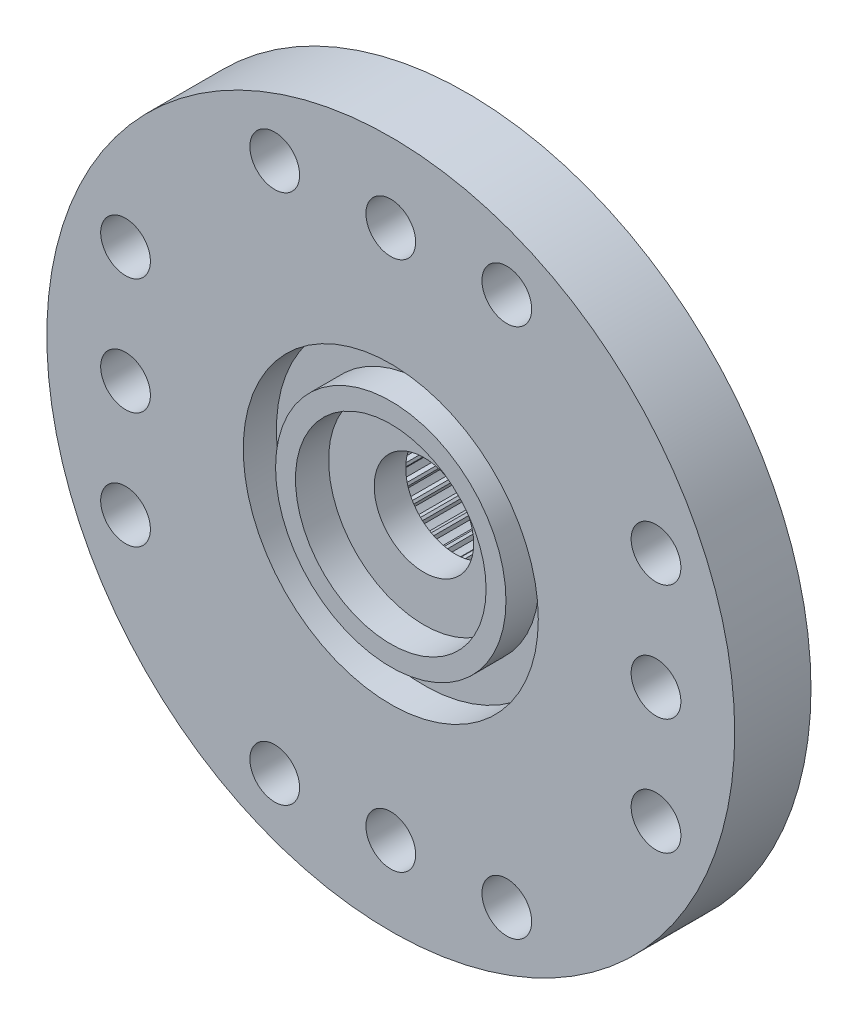
SolidWorks part; units mm, degrees
ref_plane "Plan de face" through (0, 0, 0) normal (0, 0, 1) x (1, 0, 0)
ref_plane "Plan de dessus" through (0, 0, 0) normal (0, 1, 0) x (1, 0, 0)
ref_plane "Plan de droite" through (0, 0, 0) normal (1, 0, 0) x (0, 0, -1)
sketch "Esquisse1" plane through (0, 0, 0) normal (0, 0, 1) x (1, 0, 0)
  circle A10 centre (0, 0) radius 10.375
  dimension "D7" = 20.75
extrude "Boss.-Extru.1" add sketch "Esquisse1" along normal blind 2.3
sketch "Esquisse2" plane through (0, 0, 2.3) normal (0, 0, 1) x (1, 0, 0)
  circle A0 centre (0, 0) radius 4.45
  dimension "D1" = 8.9
extrude "Enlèv. mat.-Extru.1" cut sketch "Esquisse2" against normal blind 1
sketch "Esquisse3" plane through (0, 0, 1.3) normal (0, 0, 1) x (1, 0, 0)
  circle A0 centre (0, 0) radius 2.875
  circle A1 centre (0, 0) radius 3.475
  dimension "D1" = 5.75
  dimension "D2" = 0.6
extrude "Boss.-Extru.2" add sketch "Esquisse3" along normal up to surface (1 mm away) up to face at (4.45, 0, 2.3)
sketch "Esquisse4" plane through (0, 0, 0) normal (0, 0, -1) x (-1, 0, 0)
  circle A0 centre (0, 0) radius 4.4
  dimension "D1" = 8.8
extrude "Boss.-Extru.3" add sketch "Esquisse4" along normal blind 3
sketch "Esquisse5" plane through (0, 0, 1.3) normal (0, 0, 1) x (1, 0, 0)
  circle A0 centre (0, 0) radius 1.5
  dimension "D1" = 3
extrude "Enlèv. mat.-Extru.2" cut sketch "Esquisse5" against normal through all
sketch "Esquisse6" plane through (0, 0, -3) normal (0, 0, -1) x (-1, 0, 0)
  line L0 (-0.1143, 2.9978) -> (-0.0406, 2.8652)
  line L1 (0.0406, 2.8652) -> (0.1143, 2.9978)
  line L2 (0, 2.8652) -> (0, 0) construction
  line L3 (-0.0406, 2.8652) -> (0.0406, 2.8652)
  line L4 (0.439, 2.8316) -> (0.5304, 2.9527)
  line L5 (0.3041, 2.9846) -> (0.3585, 2.8429)
  line L6 (0.3585, 2.8429) -> (0.439, 2.8316)
  line L7 (0.8288, 2.743) -> (0.9362, 2.8502)
  line L8 (0.7165, 2.9132) -> (0.7507, 2.7654)
  line L9 (0.7507, 2.7654) -> (0.8288, 2.743)
  line L10 (1.2025, 2.6009) -> (1.3237, 2.6922)
  line L11 (1.1149, 2.7851) -> (1.1283, 2.634)
  line L12 (1.1283, 2.634) -> (1.2025, 2.6009)
  line L13 (1.5527, 2.4083) -> (1.6855, 2.4817)
  line L14 (1.4917, 2.6029) -> (1.4839, 2.4513)
  line L15 (1.4839, 2.4513) -> (1.5527, 2.4083)
  line L16 (1.8728, 2.1687) -> (2.0145, 2.223)
  line L17 (1.8394, 2.3699) -> (1.8106, 2.2209)
  line L18 (1.8106, 2.2209) -> (1.8728, 2.1687)
  line L19 (2.1564, 1.887) -> (2.3043, 1.921)
  line L20 (2.1514, 2.0909) -> (2.1021, 1.9473)
  line L21 (2.1021, 1.9473) -> (2.1564, 1.887)
  line L22 (2.398, 1.5685) -> (2.5492, 1.5816)
  line L23 (2.4214, 1.7711) -> (2.3526, 1.6358)
  line L24 (2.3526, 1.6358) -> (2.398, 1.5685)
  line L25 (2.593, 1.2195) -> (2.7445, 1.2114)
  line L26 (2.6443, 1.4169) -> (2.5574, 1.2925)
  line L27 (2.5574, 1.2925) -> (2.593, 1.2195)
  line L28 (2.7375, 0.8468) -> (2.8864, 0.8177)
  line L29 (2.8158, 1.0351) -> (2.7124, 0.924)
  line L30 (2.7124, 0.924) -> (2.7375, 0.8468)
  line L31 (2.8287, 0.4575) -> (2.9721, 0.408)
  line L32 (2.9324, 0.6331) -> (2.8146, 0.5375)
  line L33 (2.8146, 0.5375) -> (2.8287, 0.4575)
  line L34 (2.8648, 0.0594) -> (3, -0.0096)
  line L35 (2.992, 0.2188) -> (2.862, 0.1406)
  line L36 (2.862, 0.1406) -> (2.8648, 0.0594)
  line L37 (2.8452, -0.3399) -> (2.9695, -0.427)
  line L38 (2.9933, -0.1997) -> (2.8537, -0.2591)
  line L39 (2.8537, -0.2591) -> (2.8452, -0.3399)
  line L40 (2.7702, -0.7325) -> (2.8811, -0.8361)
  line L41 (2.9364, -0.6144) -> (2.7899, -0.6537)
  line L42 (2.7899, -0.6537) -> (2.7702, -0.7325)
  line L43 (2.6413, -1.111) -> (2.7367, -1.229)
  line L44 (2.8223, -1.017) -> (2.6717, -1.0357)
  line L45 (2.6717, -1.0357) -> (2.6413, -1.111)
  line L46 (2.461, -1.4677) -> (2.5391, -1.5979)
  line L47 (2.6533, -1.3999) -> (2.5016, -1.3974)
  line L48 (2.5016, -1.3974) -> (2.461, -1.4677)
  line L49 (2.2328, -1.796) -> (2.292, -1.9357)
  line L50 (2.4327, -1.7556) -> (2.2828, -1.732)
  line L51 (2.2828, -1.732) -> (2.2328, -1.796)
  line L52 (1.9611, -2.0892) -> (2.0003, -2.2358)
  line L53 (2.1647, -2.0771) -> (2.0195, -2.0328)
  line L54 (2.0195, -2.0328) -> (1.9611, -2.0892)
  line L55 (1.6512, -2.3418) -> (1.6696, -2.4925)
  line L56 (1.8545, -2.3581) -> (1.7169, -2.2941)
  line L57 (1.7169, -2.2941) -> (1.6512, -2.3418)
  line L58 (1.3093, -2.5488) -> (1.3065, -2.7006)
  line L59 (1.5083, -2.5933) -> (1.381, -2.5107)
  line L60 (1.381, -2.5107) -> (1.3093, -2.5488)
  line L61 (0.9418, -2.7063) -> (0.9179, -2.8561)
  line L62 (1.1327, -2.7779) -> (1.0181, -2.6785)
  line L63 (1.0181, -2.6785) -> (0.9418, -2.7063)
  line L64 (0.556, -2.811) -> (0.5115, -2.9561)
  line L65 (0.7351, -2.9086) -> (0.6354, -2.7941)
  line L66 (0.6354, -2.7941) -> (0.556, -2.811)
  line L67 (0.1594, -2.861) -> (0.0951, -2.9985)
  line L68 (0.3231, -2.9825) -> (0.2404, -2.8553)
  line L69 (0.2404, -2.8553) -> (0.1594, -2.861)
  line L70 (-0.2404, -2.8553) -> (-0.3231, -2.9825)
  line L71 (-0.0951, -2.9985) -> (-0.1594, -2.861)
  line L72 (-0.1594, -2.861) -> (-0.2404, -2.8553)
  line L73 (-0.6354, -2.7941) -> (-0.7351, -2.9086)
  line L74 (-0.5115, -2.9561) -> (-0.556, -2.811)
  line L75 (-0.556, -2.811) -> (-0.6354, -2.7941)
  line L76 (-1.0181, -2.6785) -> (-1.1327, -2.7779)
  line L77 (-0.9179, -2.8561) -> (-0.9418, -2.7063)
  line L78 (-0.9418, -2.7063) -> (-1.0181, -2.6785)
  line L79 (-1.381, -2.5107) -> (-1.5083, -2.5933)
  line L80 (-1.3065, -2.7006) -> (-1.3093, -2.5488)
  line L81 (-1.3093, -2.5488) -> (-1.381, -2.5107)
  line L82 (-1.7169, -2.2941) -> (-1.8545, -2.3581)
  line L83 (-1.6696, -2.4925) -> (-1.6512, -2.3418)
  line L84 (-1.6512, -2.3418) -> (-1.7169, -2.2941)
  line L85 (-2.0195, -2.0328) -> (-2.1647, -2.0771)
  line L86 (-2.0003, -2.2358) -> (-1.9611, -2.0892)
  line L87 (-1.9611, -2.0892) -> (-2.0195, -2.0328)
  line L88 (-2.2828, -1.732) -> (-2.4327, -1.7556)
  line L89 (-2.292, -1.9357) -> (-2.2328, -1.796)
  line L90 (-2.2328, -1.796) -> (-2.2828, -1.732)
  line L91 (-2.5016, -1.3974) -> (-2.6533, -1.3999)
  line L92 (-2.5391, -1.5979) -> (-2.461, -1.4677)
  line L93 (-2.461, -1.4677) -> (-2.5016, -1.3974)
  line L94 (-2.6717, -1.0357) -> (-2.8223, -1.017)
  line L95 (-2.7367, -1.229) -> (-2.6413, -1.111)
  line L96 (-2.6413, -1.111) -> (-2.6717, -1.0357)
  line L97 (-2.7899, -0.6537) -> (-2.9364, -0.6144)
  line L98 (-2.8811, -0.8361) -> (-2.7702, -0.7325)
  line L99 (-2.7702, -0.7325) -> (-2.7899, -0.6537)
  line L100 (-2.8537, -0.2591) -> (-2.9933, -0.1997)
  line L101 (-2.9695, -0.427) -> (-2.8452, -0.3399)
  line L102 (-2.8452, -0.3399) -> (-2.8537, -0.2591)
  line L103 (-2.862, 0.1406) -> (-2.992, 0.2188)
  line L104 (-3, -0.0096) -> (-2.8648, 0.0594)
  line L105 (-2.8648, 0.0594) -> (-2.862, 0.1406)
  line L106 (-2.8146, 0.5375) -> (-2.9324, 0.6331)
  line L107 (-2.9721, 0.408) -> (-2.8287, 0.4575)
  line L108 (-2.8287, 0.4575) -> (-2.8146, 0.5375)
  line L109 (-2.7124, 0.924) -> (-2.8158, 1.0351)
  line L110 (-2.8864, 0.8177) -> (-2.7375, 0.8468)
  line L111 (-2.7375, 0.8468) -> (-2.7124, 0.924)
  line L112 (-2.5574, 1.2925) -> (-2.6443, 1.4169)
  line L113 (-2.7445, 1.2114) -> (-2.593, 1.2195)
  line L114 (-2.593, 1.2195) -> (-2.5574, 1.2925)
  line L115 (-2.3526, 1.6358) -> (-2.4214, 1.7711)
  line L116 (-2.5492, 1.5816) -> (-2.398, 1.5685)
  line L117 (-2.398, 1.5685) -> (-2.3526, 1.6358)
  line L118 (-2.1021, 1.9473) -> (-2.1514, 2.0909)
  line L119 (-2.3043, 1.921) -> (-2.1564, 1.887)
  line L120 (-2.1564, 1.887) -> (-2.1021, 1.9473)
  line L121 (-1.8106, 2.2209) -> (-1.8394, 2.3699)
  line L122 (-2.0145, 2.223) -> (-1.8728, 2.1687)
  line L123 (-1.8728, 2.1687) -> (-1.8106, 2.2209)
  line L124 (-1.4839, 2.4513) -> (-1.4917, 2.6029)
  line L125 (-1.6855, 2.4817) -> (-1.5527, 2.4083)
  line L126 (-1.5527, 2.4083) -> (-1.4839, 2.4513)
  line L127 (-1.1283, 2.634) -> (-1.1149, 2.7851)
  line L128 (-1.3237, 2.6922) -> (-1.2025, 2.6009)
  line L129 (-1.2025, 2.6009) -> (-1.1283, 2.634)
  line L130 (-0.7507, 2.7654) -> (-0.7165, 2.9132)
  line L131 (-0.9362, 2.8502) -> (-0.8288, 2.743)
  line L132 (-0.8288, 2.743) -> (-0.7507, 2.7654)
  line L133 (-0.3585, 2.8429) -> (-0.3041, 2.9846)
  line L134 (-0.5304, 2.9527) -> (-0.439, 2.8316)
  line L135 (-0.439, 2.8316) -> (-0.3585, 2.8429)
  circle A0 centre (0, 0) radius 3
  point P187 (0, 0)
  dimension "D1" = 6
  dimension "D2" = 45
extrude "Enlèv. mat.-Extru.3" cut sketch "Esquisse6" against normal blind 3.35
sketch "Esquisse7" plane through (0, 0, 2.3) normal (0, 0, 1) x (1, 0, 0)
  line L1 (0, 0) -> (0, 8) construction
  circle A9 centre (-8, 0) radius 0.75
  circle A26 centre (0, 0) radius 8 construction
  circle A28 centre (-8, 3.5) radius 0.75
  circle A29 centre (-8, -3.5) radius 0.75
  circle A30 centre (0, 8) radius 0.75
  circle A31 centre (3.5, 8) radius 0.75
  circle A32 centre (-3.5, 8) radius 0.75
  circle A33 centre (8, 0) radius 0.75
  circle A34 centre (8, -3.5) radius 0.75
  circle A35 centre (8, 3.5) radius 0.75
  circle A36 centre (0, -8) radius 0.75
  circle A37 centre (-3.5, -8) radius 0.75
  circle A38 centre (3.5, -8) radius 0.75
  point P1 (-0.9336, 0)
  point P6 (0.8365, 9.3461)
  point P7 (0, 0)
  point P28 (0, 0)
  point P29 (0, 0)
  dimension "D1" = 1.5
  dimension "D2" = 8
  dimension "D6" = 16
  dimension "D3" = 4
  dimension "D4" = 2
  dimension "D5" = 2
  dimension "D7" = 3.5
  dimension "D8" = 3.5
extrude "Enlèv. mat.-Extru.4" cut sketch "Esquisse7" against normal blind 3.35
